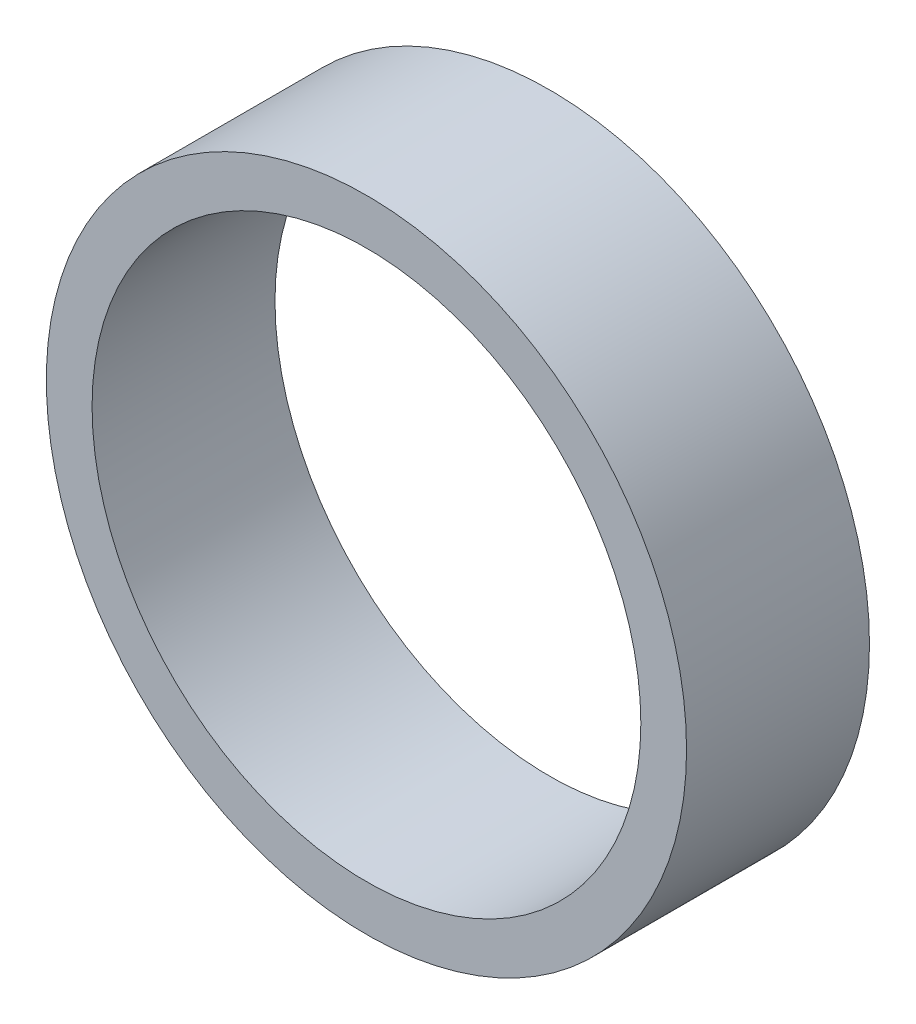
SolidWorks part; units mm, degrees
ref_plane "Front Plane" through (0, 0, 0) normal (0, 0, 1) x (1, 0, 0)
ref_plane "Top Plane" through (0, 0, 0) normal (0, 1, 0) x (1, 0, 0)
ref_plane "Right Plane" through (0, 0, 0) normal (1, 0, 0) x (0, 0, -1)
sketch "Sketch1" plane through (0, 0, 0) normal (0, 0, 1) x (1, 0, 0)
  circle A0 centre (0, 0) radius 60
  circle A1 centre (0, 0) radius 70
extrude "Boss-Extrude1" add sketch "Sketch1" along normal mid plane 40
